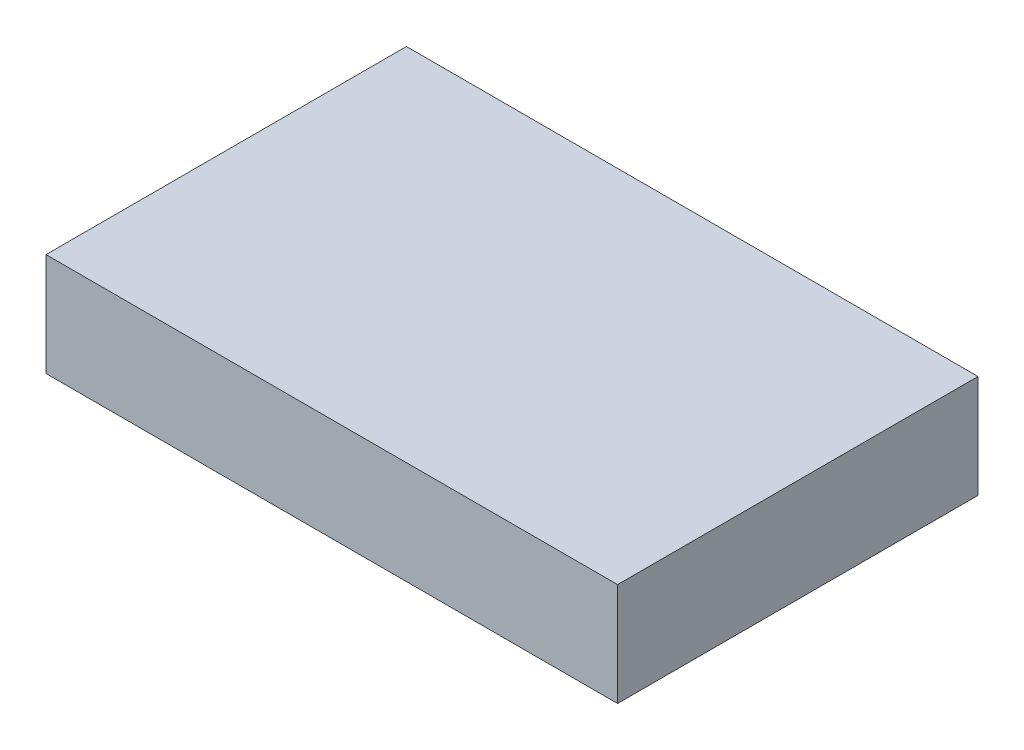
SolidWorks part; units mm, degrees
ref_plane "前视基准面" through (0, 0, 0) normal (0, 0, 1) x (1, 0, 0)
ref_plane "上视基准面" through (0, 0, 0) normal (0, 1, 0) x (1, 0, 0)
ref_plane "右视基准面" through (0, 0, 0) normal (1, 0, 0) x (0, 0, -1)
sketch "草图1" plane through (0, 0, 0) normal (0, 1, 0) x (1, 0, 0)
  line L1 (0, 0) -> (111, 0)
  line L2 (0, 0) -> (0, -70)
  line L3 (0, -70) -> (111, -70)
  line L4 (111, 0) -> (111, -70)
extrude "凸台-拉伸1" add sketch "草图1" along normal blind 20
